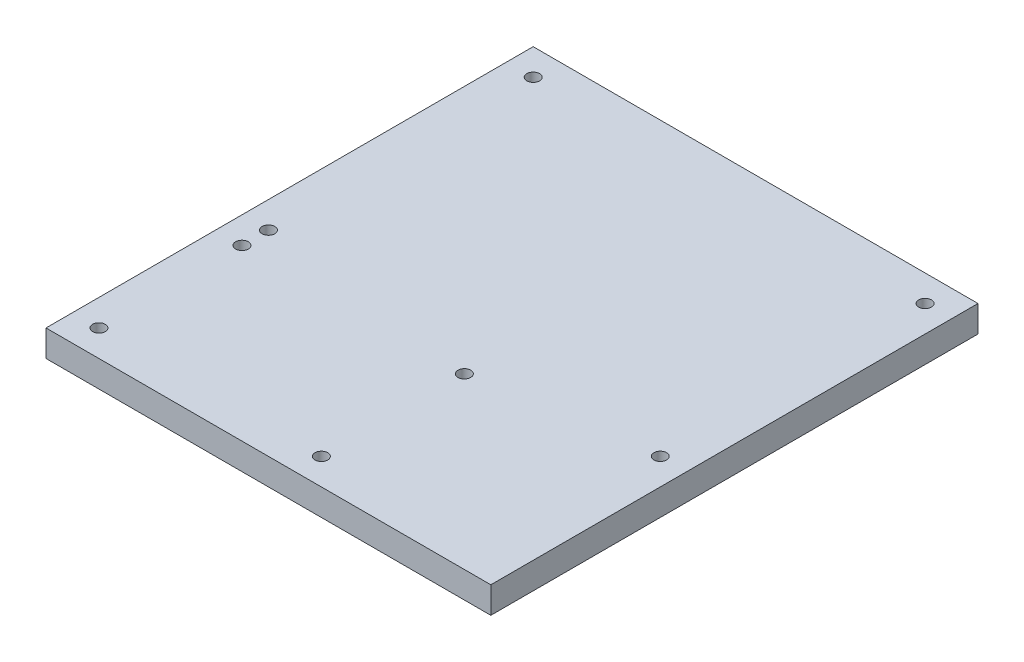
SolidWorks part; units mm, degrees
ref_plane "Front" through (0, 0, 0) normal (0, 0, 1) x (1, 0, 0)
ref_plane "Top" through (0, 0, 0) normal (0, 1, 0) x (1, 0, 0)
ref_plane "Right" through (0, 0, 0) normal (1, 0, 0) x (0, 0, -1)
sketch "草图1" plane through (0, 0, 0) normal (0, 1, 0) x (1, 0, 0)
  line L1 (-42, 46) -> (42, 46)
  line L2 (-42, 46) -> (-42, -46)
  line L3 (-42, -46) -> (42, -46)
  line L4 (42, 46) -> (42, -46)
  line L5 (-42, 46) -> (42, -46) construction
  line L6 (-42, -46) -> (42, 46) construction
  point P0 (0, 0)
  dimension "D1" = 84
  dimension "D2" = 92
extrude "凸台-拉伸1" add sketch "草图1" along normal blind 5
sketch "草图2" plane through (0, 0, 0) normal (0, -1, 0) x (1, 0, 0)
  line L1 (-2.55, 2.5) -> (2.55, 2.5)
  line L2 (-2.55, 2.5) -> (-2.55, -2.5)
  line L3 (-2.55, -2.5) -> (2.55, -2.5)
  line L4 (2.55, 2.5) -> (2.55, -2.5)
  line L5 (-2.55, 2.5) -> (2.55, -2.5) construction
  line L6 (-2.55, -2.5) -> (2.55, 2.5) construction
  line L7 (-7.5, 7.5) -> (7.5, 7.5)
  line L8 (-7.5, 7.5) -> (-7.5, -7.5)
  line L9 (-7.5, -7.5) -> (7.5, -7.5)
  line L10 (7.5, 7.5) -> (7.5, -7.5)
  line L11 (-7.5, 7.5) -> (7.5, -7.5) construction
  line L12 (-7.5, -7.5) -> (7.5, 7.5) construction
  line L13 (12.5, -12.5) -> (-12.5, -12.5)
  line L14 (12.5, -12.5) -> (12.5, 12.5)
  line L15 (12.5, 12.5) -> (-12.5, 12.5)
  line L16 (-12.5, -12.5) -> (-12.5, 12.5)
  line L17 (12.5, -12.5) -> (-12.5, 12.5) construction
  line L18 (12.5, 12.5) -> (-12.5, -12.5) construction
  point P0 (0, 0)
  point P6 (0, 0)
  point P11 (0, 0)
  dimension "D1" = 5.1
  dimension "D2" = 5
  dimension "D3" = 15
  dimension "D4" = 25
  dimension "D5" = 25
extrude "凸台-拉伸2" add sketch "草图2" along normal blind 10 contours L16 L13 L14 L15 L7 L10 L9 L8 | L4 L1 L2 L3
sketch "草图3" plane through (0, 5, 0) normal (0, 1, 0) x (1, 0, 0)
  line L0 (-37, 41) -> (37, 41) construction
  line L1 (37, 41) -> (37, -9) construction
  line L2 (37, -9) -> (-37, -9) construction
  line L3 (-37, -9) -> (-37, 41) construction
  line L4 (42, 46) -> (-42, 46) construction
  line L5 (-42, 46) -> (-42, -46) construction
  line L6 (-37, -14) -> (5, -14) construction
  line L7 (5, -14) -> (5, -41) construction
  line L8 (5, -41) -> (-37, -41) construction
  line L9 (-37, -41) -> (-37, -14) construction
  line L10 (-42, -46) -> (42, -46) construction
  circle A0 centre (-37, -14) radius 1.2
  circle A1 centre (5, -14) radius 1.2
  circle A2 centre (-37, -41) radius 1.2
  circle A3 centre (5, -41) radius 1.2
  circle A4 centre (37, -9) radius 1.2
  circle A5 centre (-37, -9) radius 1.2
  circle A6 centre (-37, 41) radius 1.2
  circle A7 centre (37, 41) radius 1.2
  dimension "D9" = 2.4
  dimension "D1" = 5
  dimension "D2" = 5
  dimension "D3" = 74
  dimension "D4" = 50
  dimension "D5" = 5
  dimension "D6" = 27
  dimension "D7" = 42
  dimension "D8" = 5
extrude "切除-拉伸1" cut sketch "草图3" against normal blind 10
